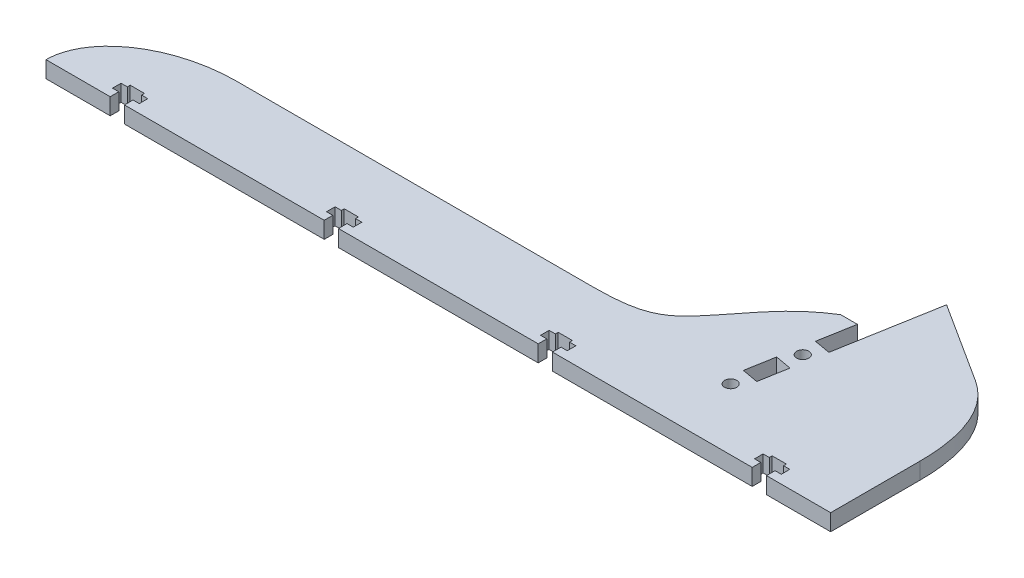
SolidWorks part; units mm, degrees
ref_plane "Front Plane" through (0, 0, 0) normal (0, 0, 1) x (1, 0, 0)
ref_plane "Top Plane" through (0, 0, 0) normal (0, 1, 0) x (1, 0, 0)
ref_plane "Right Plane" through (0, 0, 0) normal (1, 0, 0) x (0, 0, -1)
sketch "Sketch1" plane through (0, 0, 0) normal (0, 1, 0) x (1, 0, 0)
  line L0 (25.4, -57.404) -> (25.4, -56.388)
  line L1 (20.6375, -57.404) -> (30.1625, -57.404)
  line L2 (0, 0) -> (279.4, 0)
  line L3 (0, 0) -> (0, -63.5)
  line L4 (0, -63.5) -> (279.4, -63.5)
  line L5 (279.4, 0) -> (279.4, -63.5)
  line L6 (22.86, -63.5) -> (27.94, -63.5)
  line L7 (22.86, -63.5) -> (22.86, -56.388)
  line L8 (22.86, -56.388) -> (27.94, -56.388)
  line L9 (27.94, -63.5) -> (27.94, -56.388)
  line L10 (20.6375, -57.404) -> (20.6375, -60.452)
  line L11 (20.6375, -60.452) -> (30.1625, -60.452)
  line L12 (30.1625, -57.404) -> (30.1625, -60.452)
  line L13 (25.4, -60.452) -> (25.4, -63.5)
  line L14 (101.6, -57.404) -> (101.6, -56.388)
  line L15 (96.8375, -57.404) -> (106.3625, -57.404)
  line L16 (99.06, -63.5) -> (104.14, -63.5)
  line L17 (99.06, -63.5) -> (99.06, -56.388)
  line L18 (99.06, -56.388) -> (104.14, -56.388)
  line L19 (104.14, -63.5) -> (104.14, -56.388)
  line L20 (96.8375, -57.404) -> (96.8375, -60.452)
  line L21 (96.8375, -60.452) -> (106.3625, -60.452)
  line L22 (106.3625, -57.404) -> (106.3625, -60.452)
  line L23 (101.6, -60.452) -> (101.6, -63.5)
  line L24 (177.8, -57.404) -> (177.8, -56.388)
  line L25 (173.0375, -57.404) -> (182.5625, -57.404)
  line L26 (175.26, -63.5) -> (180.34, -63.5)
  line L27 (175.26, -63.5) -> (175.26, -56.388)
  line L28 (220.98, -63.5) -> (240.4627, 46.9919) construction
  line L29 (175.26, -56.388) -> (180.34, -56.388)
  line L30 (220.98, -63.5) -> (215.1767, -62.4767) construction
  line L31 (180.34, -63.5) -> (180.34, -56.388)
  line L32 (173.0375, -57.404) -> (173.0375, -60.452)
  line L33 (227.5681, -26.1369) -> (221.7648, -25.1136)
  line L34 (173.0375, -60.452) -> (182.5625, -60.452)
  line L35 (182.5625, -57.404) -> (182.5625, -60.452)
  line L36 (177.8, -60.452) -> (177.8, -63.5)
  line L37 (254, -57.404) -> (254, -56.388)
  line L38 (249.2375, -57.404) -> (258.7625, -57.404)
  line L39 (251.46, -63.5) -> (256.54, -63.5)
  line L40 (251.46, -63.5) -> (251.46, -56.388)
  line L41 (251.46, -56.388) -> (256.54, -56.388)
  line L42 (256.54, -63.5) -> (256.54, -56.388)
  line L43 (249.2375, -57.404) -> (249.2375, -60.452)
  line L44 (249.2375, -60.452) -> (258.7625, -60.452)
  line L45 (258.7625, -57.404) -> (258.7625, -60.452)
  line L46 (254, -60.452) -> (254, -63.5)
  line L47 (254, -56.388) -> (279.4, -56.388) construction
  line L48 (177.8, -57.404) -> (279.4, -57.404) construction
  line L49 (101.6, -60.452) -> (279.4, -60.452) construction
  line L50 (25.4, -61.976) -> (279.4, -61.976) construction
  line L54 (227.5681, -26.1369) -> (225.7923, -36.2083)
  line L55 (221.7648, -25.1136) -> (219.989, -35.185)
  line L56 (225.7923, -36.2083) -> (219.989, -35.185)
  line L57 (229.6411, -14.3803) -> (223.8379, -13.357)
  line L58 (223.8379, -13.357) -> (226.078, -0.6524)
  line L59 (231.8813, -1.6757) -> (226.078, -0.6524) construction
  line L60 (40.6643, -36.2083) -> (167.647, -36.2083)
  line L61 (226.078, -0.6524) -> (220.1063, -0.6524)
  line L62 (229.6411, -14.3803) -> (233.1239, 5.3716)
  line L64 (233.1239, 5.3716) -> (237.4671, 30.0031)
  line L67 (235.9229, 21.2457) -> (270.3272, -0.7788)
  line L68 (228.9797, -1.1641) -> (218.0784, -62.9884) construction
  circle A0 centre (225.703, -19.7469) radius 2.159
  circle A1 centre (221.8541, -41.575) radius 2.159
  ellipse E1 centre (40.6643, -63.5) end of major axis (81.3285, -63.5) minor radius 27.2917 (40.6643, -36.2083) -> (0, -63.5) ccw
  spline S0 degree 3 poles (167.647, -36.2083) (182.5409, -36.1771) (193.4715, -31.3207) (212.3012, -0.8125) (255.5098, 15.7181) (279.375, -5.73) (279.4, -31.75) knots 0 0 0 0 0.184493 0.370391 0.670996 1 1 1 1
  dimension "D28" = 4.318
  dimension "D29" = 4.318
  dimension "D2" = 279.4
  dimension "D3" = 5.08
  dimension "D4" = 7.112
  dimension "D5" = 9.525
  dimension "D6" = 3.048
  dimension "D7" = 3.048
  dimension "D8" = 5.08
  dimension "D9" = 7.112
  dimension "D10" = 9.525
  dimension "D11" = 3.048
  dimension "D12" = 3.048
  dimension "D13" = 5.08
  dimension "D14" = 7.112
  dimension "D15" = 9.525
  dimension "D16" = 3.048
  dimension "D17" = 27.2917
  dimension "D18" = 3.048
  dimension "D19" = 5.08
  dimension "D20" = 7.112
  dimension "D21" = 9.525
  dimension "D22" = 3.048
  dimension "D23" = 3.048
  dimension "D24" = 25.4
  dimension "D25" = 101.6
  dimension "D26" = 177.8
  dimension "D27" = 254
  dimension "D30" = 5.969
  dimension "D31" = 5.969
extrude "Boss-Extrude1" add sketch "Sketch1" along normal blind 5.8928
